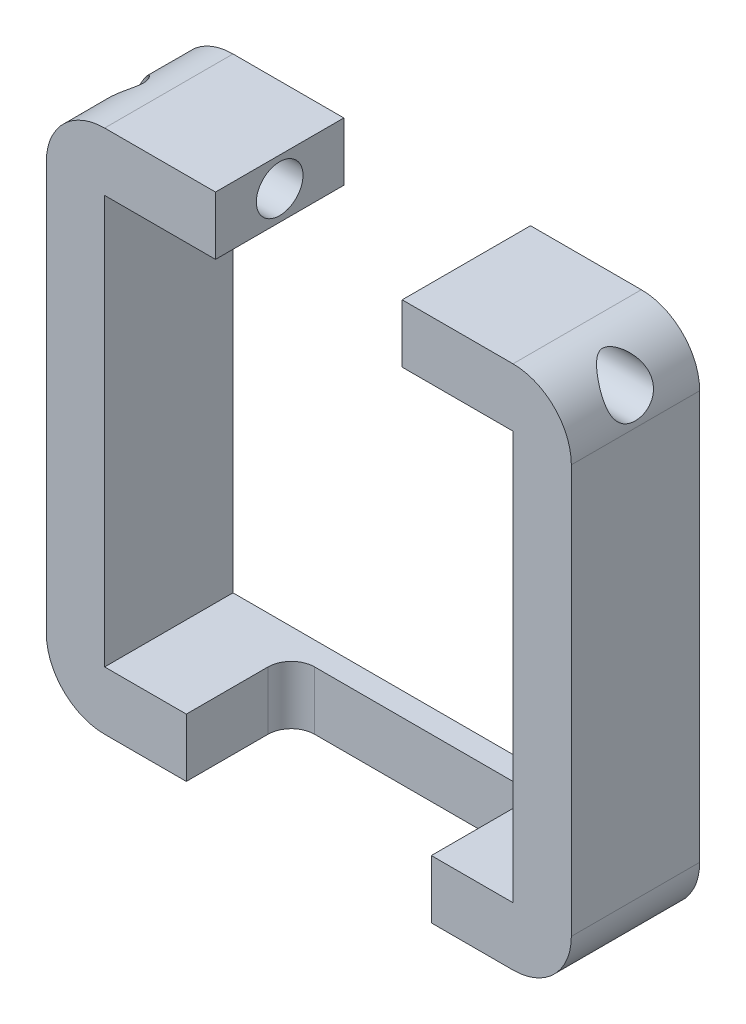
SolidWorks part; units mm, degrees
ref_plane "Plan de face" through (0, 0, 0) normal (0, 0, 1) x (1, 0, 0)
ref_plane "Plan de dessus" through (0, 0, 0) normal (0, 1, 0) x (1, 0, 0)
ref_plane "Plan de droite" through (0, 0, 0) normal (1, 0, 0) x (0, 0, -1)
sketch "Esquisse1" plane through (0, 0, 0) normal (0, 0, 1) x (1, 0, 0)
  line L0 (17.5, 17.5) -> (-17.5, 17.5)
  line L1 (17.5, -22.5) -> (-17.5, -22.5)
  line L2 (22.5, -17.5) -> (22.5, 17.5)
  line L3 (17.5, 22.5) -> (-17.5, 22.5)
  line L4 (-22.5, -17.5) -> (-22.5, 17.5)
  line L5 (22.5, -22.5) -> (-22.5, 22.5) construction
  line L6 (22.5, 22.5) -> (-22.5, -22.5) construction
  line L7 (-17.5, -17.5) -> (-17.5, 17.5)
  line L8 (17.5, -17.5) -> (-17.5, -17.5)
  line L9 (17.5, -17.5) -> (17.5, 17.5)
  line L10 (22.5, -22.5) -> (-22.5, -22.5) construction
  line L11 (-22.5, -22.5) -> (-22.5, 22.5) construction
  line L12 (22.5, -22.5) -> (22.5, 22.5) construction
  line L13 (22.5, 22.5) -> (-22.5, 22.5) construction
  arc A0 (-17.5, -22.5) -> (-22.5, -17.5) centre (-17.5, -17.5) cw
  arc A1 (17.5, -22.5) -> (22.5, -17.5) centre (17.5, -17.5) ccw
  arc A2 (22.5, 17.5) -> (17.5, 22.5) centre (17.5, 17.5) ccw
  arc A3 (-17.5, 22.5) -> (-22.5, 17.5) centre (-17.5, 17.5) ccw
  point P0 (0, 0)
  dimension "D4" = 5
  dimension "D1" = 45
  dimension "D2" = 45
  dimension "D3" = 5
extrude "Boss.-Extru.1" add sketch "Esquisse1" along normal blind 11
sketch "Esquisse2" plane through (0, 0, 11) normal (0, 0, 1) x (1, 0, 0)
  line L0 (17.5, 22.5) -> (-17.5, 22.5) construction
  line L1 (-8, 25.5) -> (8, 25.5)
  line L2 (-8, 25.5) -> (-8, 15.5)
  line L3 (-8, 15.5) -> (8, 15.5)
  line L4 (8, 25.5) -> (8, 15.5)
  line L5 (-8, 25.5) -> (8, 15.5) construction
  line L6 (-8, 15.5) -> (8, 25.5) construction
  point P0 (0, 20.5)
  point P5 (0, 0)
  point P6 (0, 19.9557)
  dimension "D1" = 16
  dimension "D2" = 10
  dimension "D3" = 2
extrude "Enlèv. mat.-Extru.1" cut sketch "Esquisse2" against normal through all
sketch "Esquisse3" plane through (-8, 0, 0) normal (1, 0, 0) x (0, 0, -1)
  line L0 (-11, 22.5) -> (-11, 17.5) construction
  line L1 (-11, 22.5) -> (0, 22.5) construction
  circle A0 centre (-5.5, 20) radius 2
  point P4 (-11, 20)
  point P7 (-5.5, 22.5)
  dimension "D1" = 4
extrude "Enlèv. mat.-Extru.2" cut sketch "Esquisse3" against normal mid plane 100
sketch "Esquisse4" plane through (0, -22.5, 0) normal (0, -1, 0) x (1, 0, 0)
  line L0 (-10.5, 11) -> (-10.5, 4)
  line L1 (-17.5, 11) -> (17.5, 11) construction
  line L2 (0, 16.1512) -> (0, -10.5942) construction
  line L3 (-8.5, 2) -> (8.5, 2)
  line L4 (10.5, 11) -> (10.5, 4)
  arc A0 (-10.5, 4) -> (-8.5, 2) centre (-8.5, 4) ccw
  arc A1 (10.5, 4) -> (8.5, 2) centre (8.5, 4) cw
  point P11 (0, 2)
  line M9 (17.5, 11) -> (-17.5, 11)
  dimension "D1" = 10.5
  dimension "D2" = 2
  dimension "D3" = 9
extrude "Enlèv. mat.-Extru.3" cut sketch "Esquisse4" against normal up to surface (40 mm away) and the other way through all contours L2 L3 A1 L4 M9 | L2 L0 A0 L3 M9 up to face at (-12.75, 17.5, 5.5)
